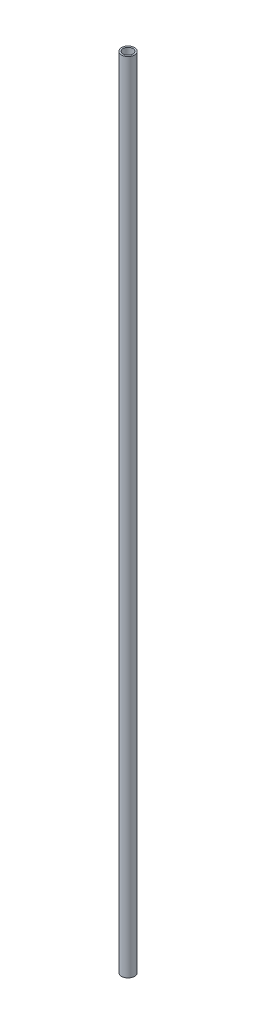
SolidWorks part; units mm, degrees
ref_plane "Front Plane" through (0, 0, 0) normal (0, 0, 1) x (1, 0, 0)
ref_plane "Top Plane" through (0, 0, 0) normal (0, 1, 0) x (1, 0, 0)
ref_plane "Right Plane" through (0, 0, 0) normal (1, 0, 0) x (0, 0, -1)
sketch "Sketch1" plane through (0, 0, 0) normal (0, 1, 0) x (1, 0, 0)
  circle A0 centre (0, 0) radius 0.6858
  circle A1 centre (0, 0) radius 0.9144
  dimension "D1" = 1.3716
  dimension "D2" = 1.8288
extrude "Boss-Extrude1" add sketch "Sketch1" along normal blind 112.7
